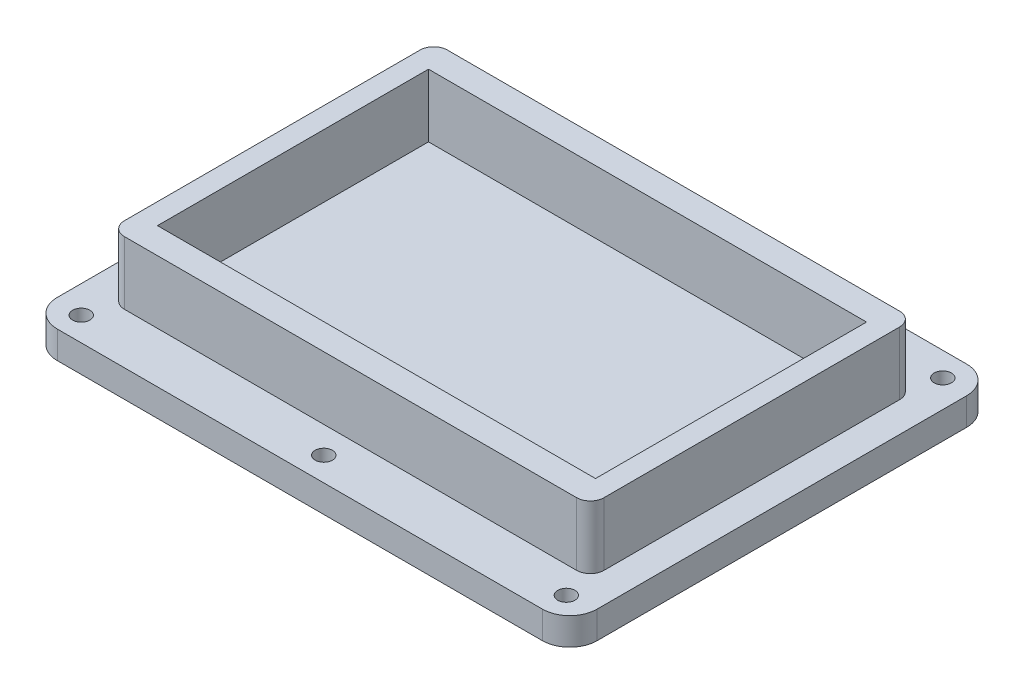
SolidWorks part; units mm, degrees
ref_plane "Front Plane" through (0, 0, 0) normal (0, 0, 1) x (1, 0, 0)
ref_plane "Top Plane" through (0, 0, 0) normal (0, 1, 0) x (1, 0, 0)
ref_plane "Right Plane" through (0, 0, 0) normal (1, 0, 0) x (0, 0, -1)
sketch "Sketch1" plane through (0, 0, 0) normal (0, 1, 0) x (1, 0, 0)
  line L1 (-64.8595, 54.2584) -> (-14.7707, 54.2584)
  line L2 (-64.8595, 54.2584) -> (-64.8595, 14.8884)
  line L3 (-64.8595, 14.8884) -> (-14.7707, 14.8884)
  line L4 (-14.7707, 54.2584) -> (-14.7707, 14.8884)
  dimension "D1" = 50.0888
  dimension "D2" = 39.37
extrude "Boss-Extrude1" add sketch "Sketch1" along normal blind 2.54
sketch "Sketch2" plane through (0, 2.54, 0) normal (0, 1, 0) x (1, 0, 0)
  line L0 (-14.7707, 54.2584) -> (-64.8595, 54.2584) construction
  line L1 (-62.0655, 49.5594) -> (-17.5647, 49.5594)
  line L2 (-62.0655, 49.5594) -> (-62.0655, 19.5874)
  line L3 (-62.0655, 19.5874) -> (-17.5647, 19.5874)
  line L4 (-17.5647, 49.5594) -> (-17.5647, 19.5874)
  line L5 (-64.8595, 14.8884) -> (-14.7707, 14.8884) construction
  line L6 (-64.8595, 54.2584) -> (-64.8595, 14.8884) construction
  line L7 (-14.7707, 14.8884) -> (-14.7707, 54.2584) construction
  dimension "D1" = 4.699
  dimension "D2" = 4.699
  dimension "D3" = 2.794
  dimension "D4" = 2.794
extrude "Boss-Extrude2" add sketch "Sketch2" along normal blind 5.842
fillet "Fillet1" radius 2.54 4 edges at (-64.8595, 1.27, -14.8884) (-14.7707, 1.27, -14.8884) (-14.7707, 1.27, -54.2584) (-64.8595, 1.27, -54.2584)
fillet "Fillet2" radius 1.27 4 edges at (-62.0655, 5.461, -19.5874) (-17.5647, 5.461, -19.5874) (-17.5647, 5.461, -49.5594) (-62.0655, 5.461, -49.5594)
hole_wizard "Ø1.6 (1.6) Diameter Hole1" positions "Sketch4" profile "Sketch3" hole size "Ø1.6" standard "ANSI Metric" end condition through all
sketch "Sketch4" plane through (0, 0, 0) normal (0, -1, 0) x (-1, 0, 0)
  line L0 (64.8595, 51.7184) -> (64.8595, 17.4284) construction
  line L1 (62.3195, 14.8884) -> (17.3107, 14.8884) construction
  line L2 (14.7707, 17.4284) -> (14.7707, 51.7184) construction
  line L3 (17.3107, 54.2584) -> (62.3195, 54.2584) construction
  point P0 (62.3195, 17.1109)
  point P2 (39.8151, 17.1109)
  point P4 (17.3107, 17.1109)
  point P6 (17.3107, 52.0359)
  point P8 (39.8151, 52.0359)
  point P10 (62.3195, 52.0359)
  point P19 (39.8151, 14.8884)
  point P22 (39.8151, 54.2584)
  dimension "D1" = 2.54
  dimension "D2" = 2.2225
  dimension "D3" = 2.2225
  dimension "D4" = 2.54
  dimension "D5" = 2.2225
  dimension "D6" = 0
  dimension "D7" = 2.2225
  dimension "D8" = 2.54
  dimension "D9" = 2.2225
  dimension "D10" = 0
  dimension "D11" = 2.54
  dimension "D12" = 2.2225
sketch "Sketch3" plane through (-62.3195, 0, -17.1109) normal (1, 0, 0) x (0, 0, -1)
  line L0 (0, 0) -> (0, 8.382)
  line L1 (0, 8.382) -> (0.8, 8.382)
  line L2 (0.8, 8.382) -> (0.8, 0)
  line L5 (0.8, 0) -> (0, 0)
  line L11 (0, -6.35) -> (0, 107.95) construction
  dimension "Thru Hole Dia." = 1.6
  dimension "Thru Hole Depth" = 8.382
sketch "Sketch5" plane through (0, 8.382, 0) normal (0, 1, 0) x (1, 0, 0)
  line L1 (-60.1351, 22.0004) -> (-19.4951, 22.0004)
  line L2 (-60.1351, 22.0004) -> (-60.1351, 47.1464)
  line L3 (-60.1351, 47.1464) -> (-19.4951, 47.1464)
  line L4 (-19.4951, 22.0004) -> (-19.4951, 47.1464)
  line L5 (-62.0655, 48.2894) -> (-62.0655, 20.8574) construction
  line L6 (-18.8347, 49.5594) -> (-60.7955, 49.5594) construction
  dimension "D1" = 25.146
  dimension "D2" = 40.64
  dimension "D3" = 1.9304
  dimension "D4" = 2.413
extrude "Cut-Extrude1" cut sketch "Sketch5" against normal blind 5.842
